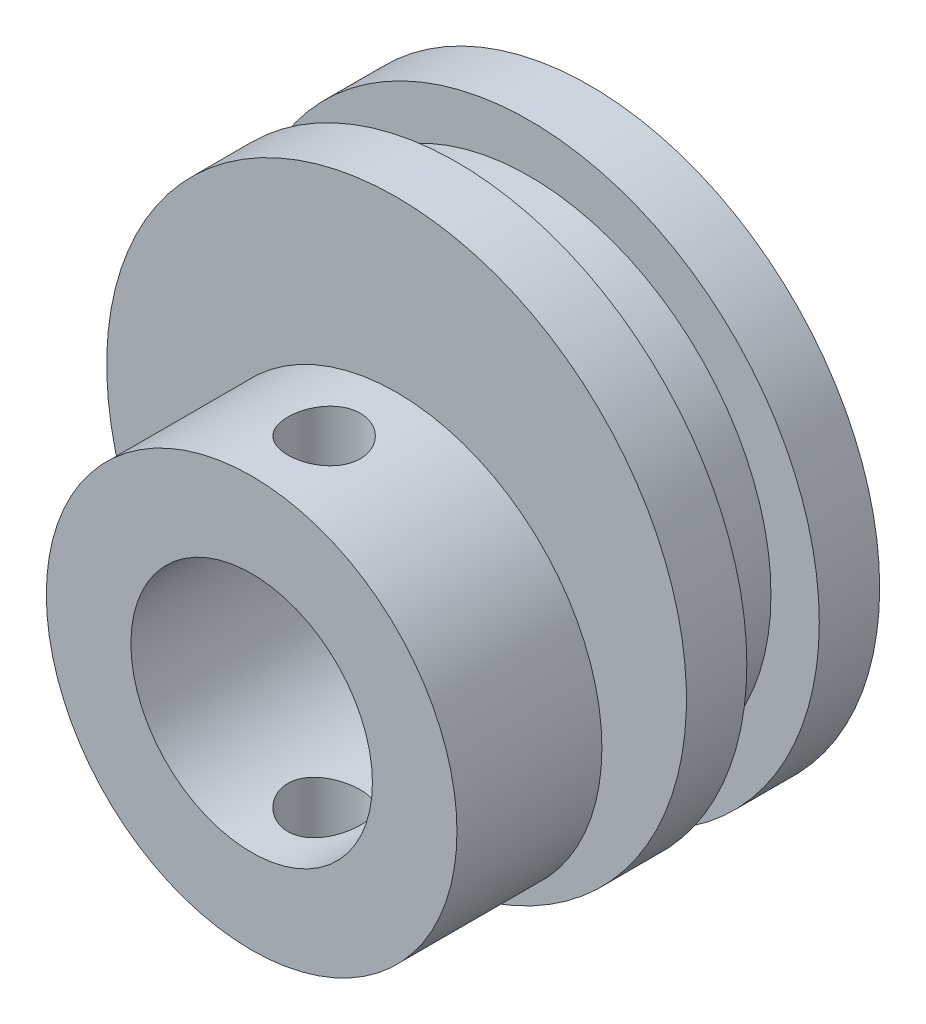
SolidWorks part; units mm, degrees
ref_plane "Front Plane" through (0, 0, 0) normal (0, 0, 1) x (1, 0, 0)
ref_plane "Top Plane" through (0, 0, 0) normal (0, 1, 0) x (1, 0, 0)
ref_plane "Right Plane" through (0, 0, 0) normal (1, 0, 0) x (0, 0, -1)
sketch "Sketch1" plane through (0, 0, 0) normal (0, 0, 1) x (1, 0, 0)
  circle A0 centre (0, 0) radius 12
  dimension "D1" = 24
extrude "Boss-Extrude1" add sketch "Sketch1" along normal mid plane 8
sketch "Sketch3" plane through (0, 0, 0) normal (1, 0, 0) x (0, 0, -1)
  line L0 (4, 12) -> (-4, 12) construction
  line L1 (-1.5, 10) -> (1.5, 10)
  line L2 (-1.5, 10) -> (-1.5, 13.3129)
  line L4 (1.5, 10) -> (1.5, 13.3129)
  line L7 (-1.5, 13.3129) -> (1.5, 13.3129)
  line L8 (0, 0) -> (-8.0415, 0) construction
  point P0 (0, 12)
  dimension "D1" = 10
revolve "Cut-Revolve2" cut sketch "Sketch3" angle 360 about L8
sketch "Sketch6" plane through (0, 0, 4) normal (0, 0, 1) x (1, 0, 0)
  circle A0 centre (0, -3.5) radius 8.5
  circle A1 centre (0, 0) radius 12 construction
  dimension "D1" = 17
  dimension "D2" = 3.5
extrude "Boss-Extrude2" add sketch "Sketch6" along normal blind 6
sketch "Sketch7" plane through (0, 0, 10) normal (0, 0, 1) x (1, 0, 0)
  circle A0 centre (0, -3.5) radius 5
  circle A1 centre (0, -3.5) radius 8.5 construction
  dimension "D1" = 10
extrude "Cut-Extrude1" cut sketch "Sketch7" against normal through all both and the other way through all
sketch "Sketch8" plane through (0, 0, 0) normal (0, 1, 0) x (1, 0, 0)
  line L0 (-8.5, -10) -> (8.5, -10) construction
  circle A0 centre (0, -7) radius 1.5
  dimension "D1" = 3
  dimension "D2" = 3
extrude "Cut-Extrude2" cut sketch "Sketch8" against normal through all both and the other way through all
